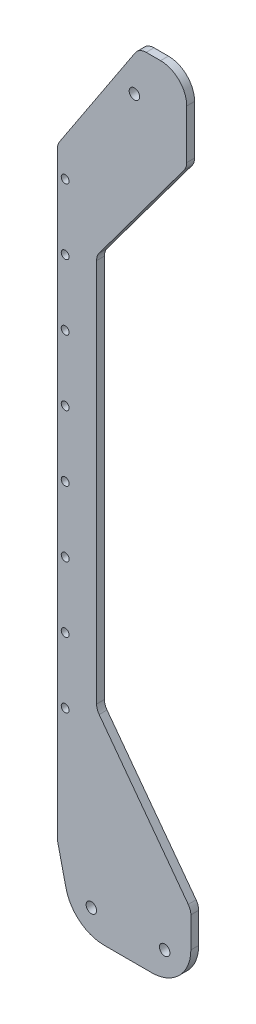
SolidWorks part; units mm, degrees
material "A-玻璃纤维"
ref_plane "前视基准面" through (0, 0, 0) normal (0, 0, 1) x (1, 0, 0)
ref_plane "上视基准面" through (0, 0, 0) normal (0, 1, 0) x (1, 0, 0)
ref_plane "右视基准面" through (0, 0, 0) normal (1, 0, 0) x (0, 0, -1)
other "Configuration Table"
sketch "草图1" plane through (0, 0, 0) normal (0, 0, 1) x (1, 0, 0)
  line L0 (0, 0) -> (36, 0)
  line L1 (36, 0) -> (36, 28.2699)
  line L2 (36, 28.2699) -> (0, 76.7026)
  line L3 (0, 76.7026) -> (0, 226.7026)
  line L4 (0, 226.7026) -> (34.4368, 273.0324)
  line L5 (34.4368, 273.0324) -> (34.4368, 303.4053)
  line L6 (34.4368, 303.4053) -> (16.2322, 303.4053)
  line L7 (16.2322, 303.4053) -> (-15, 256)
  line L8 (-15, 256) -> (-15, 26)
  line L10 (47.9663, 151.7026) -> (-87.2585, 151.7026) construction
  line L11 (-9, 0) -> (0, 0)
  line L12 (-15, 26) -> (-9, 0)
  circle A0 centre (26, 10) radius 2
  circle A1 centre (14.4368, 287.4053) radius 2
  circle A2 centre (-2, 10) radius 2
  point P11 (9.1679, 308.6812)
  point P19 (11.5097, 309.5217)
  point P20 (35.8525, 284.7965)
  point P21 (14.1861, 310.5412)
  point P24 (34.4368, 277.8111)
  point P25 (-15, 276.0057)
  point P26 (-15, 265.5632)
  point P27 (0, 231.4134)
  dimension "D3" = 4
  dimension "D9" = 4
  dimension "D14" = 4
  dimension "D1" = 10
  dimension "D2" = 10
  dimension "D4" = 16
  dimension "D5" = 15
  dimension "D6" = 20
  dimension "D7" = 36
  dimension "D8" = 57.7264
  dimension "D10" = 18.2046
  dimension "D11" = 150
  dimension "D12" = 56.769
  dimension "D13" = 26.6833
  dimension "D15" = 13
  dimension "D16" = 9
  dimension "D17" = 230
  dimension "D18" = 48.4328
extrude "凸台-拉伸1" add sketch "草图1" along normal blind 3
sketch "草图2" plane through (0, 0, 3) normal (0, 0, 1) x (1, 0, 0)
  line L0 (-12, 287.3281) -> (-12, 16.752) construction
  line L1 (-15, 256) -> (-15, 26) construction
  circle A0 centre (-12, 246) radius 1.5
  circle A1 centre (-12, 221) radius 1.5
  circle A2 centre (-12, 196) radius 1.5
  circle A3 centre (-12, 171) radius 1.5
  circle A4 centre (-12, 146) radius 1.5
  circle A5 centre (-12, 121) radius 1.5
  circle A6 centre (-12, 96) radius 1.5
  circle A7 centre (-12, 71) radius 1.5
  dimension "D1" = 3
  dimension "D2" = 3
  dimension "D4" = 25
  dimension "D5" = 10
  dimension "D3" = 8
extrude "切除-拉伸1" cut sketch "草图2" against normal through all
fillet "圆角1" radius 15 2 edges at (36, 0, 1.5) (-9, 0, 1.5)
fillet "圆角2" radius 5 7 edges at (-15, 26, 1.5) (-15, 256, 1.5) (16.2322, 303.4053, 1.5) (34.4368, 273.0324, 1.5) (0, 226.7026, 1.5) (0, 76.7026, 1.5) (36, 28.2699, 1.5)
fillet "圆角3" radius 10 1 edges at (34.4368, 303.4053, 1.5)
